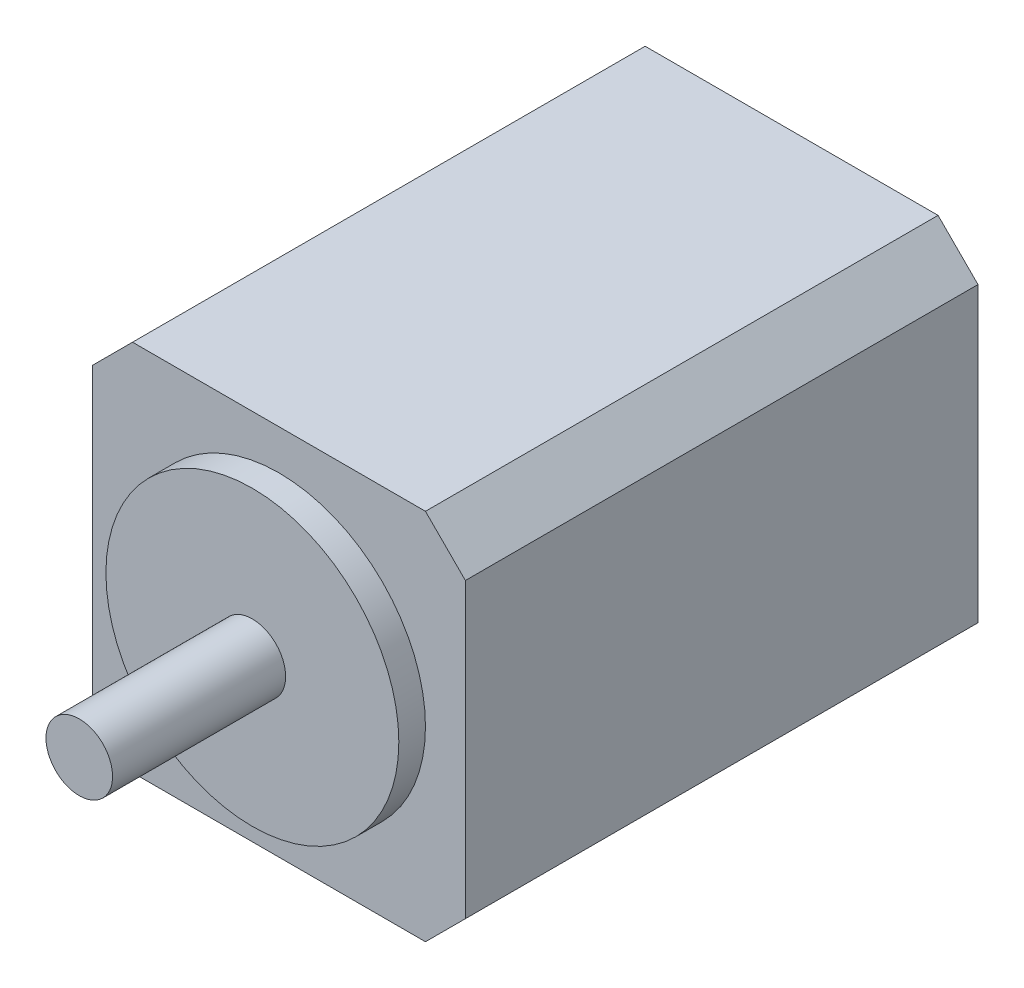
SolidWorks part; units mm, degrees
ref_plane "前视基准面" through (0, 0, 0) normal (0, 0, 1) x (1, 0, 0)
ref_plane "上视基准面" through (0, 0, 0) normal (0, 1, 0) x (1, 0, 0)
ref_plane "右视基准面" through (0, 0, 0) normal (1, 0, 0) x (0, 0, -1)
other "Configuration Table"
sketch "草图1" plane through (0, 0, 0) normal (0, 0, 1) x (1, 0, 0)
  line L1 (-14, -14) -> (14, -14)
  line L2 (-14, -14) -> (-14, 14)
  line L3 (-14, 14) -> (14, 14)
  line L4 (14, -14) -> (14, 14)
  line L5 (-14, -14) -> (14, 14) construction
  line L6 (-14, 14) -> (14, -14) construction
  point P0 (0, 0)
  dimension "D1" = 28
  dimension "D2" = 28
extrude "凸台-拉伸1" add sketch "草图1" along normal blind 38.5
sketch "草图2" plane through (0, 0, 38.5) normal (0, 0, 1) x (1, 0, 0)
  circle A0 centre (0, 0) radius 11
  dimension "D1" = 22
extrude "凸台-拉伸2" add sketch "草图2" along normal blind 2
sketch "草图3" plane through (0, 0, 40.5) normal (0, 0, 1) x (1, 0, 0)
  circle A0 centre (0, 0) radius 2.5
  dimension "D1" = 5
extrude "凸台-拉伸3" add sketch "草图3" along normal blind 13
chamfer "倒角1" distance 3 angle 45 4 edges at (-14, -14, 19.25) (-14, 14, 19.25) (14, -14, 19.25) (14, 14, 19.25)
